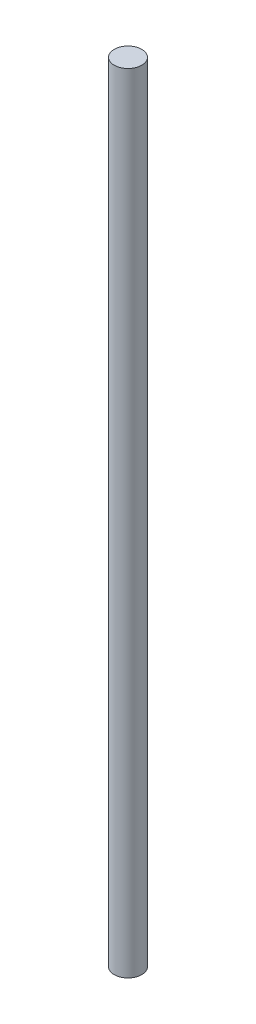
SolidWorks part; units mm, degrees
ref_plane "Front Plane" through (0, 0, 0) normal (0, 0, 1) x (1, 0, 0)
ref_plane "Top Plane" through (0, 0, 0) normal (0, 1, 0) x (1, 0, 0)
ref_plane "Right Plane" through (0, 0, 0) normal (1, 0, 0) x (0, 0, -1)
sketch "Sketch1" plane through (0, 0, 0) normal (0, 1, 0) x (1, 0, 0)
  circle A0 centre (0, 0) radius 3.5
  dimension "D1" = 7
extrude "Boss-Extrude1" add sketch "Sketch1" along normal blind 200
sketch "Sketch3" plane through (0, 0, 0) normal (0, -1, 0) x (1, 0, 0)
  point P0 (0, 0)
sketch "Sketch4" plane through (0, 200, 0) normal (0, 1, 0) x (1, 0, 0)
  point P0 (0, 0)
